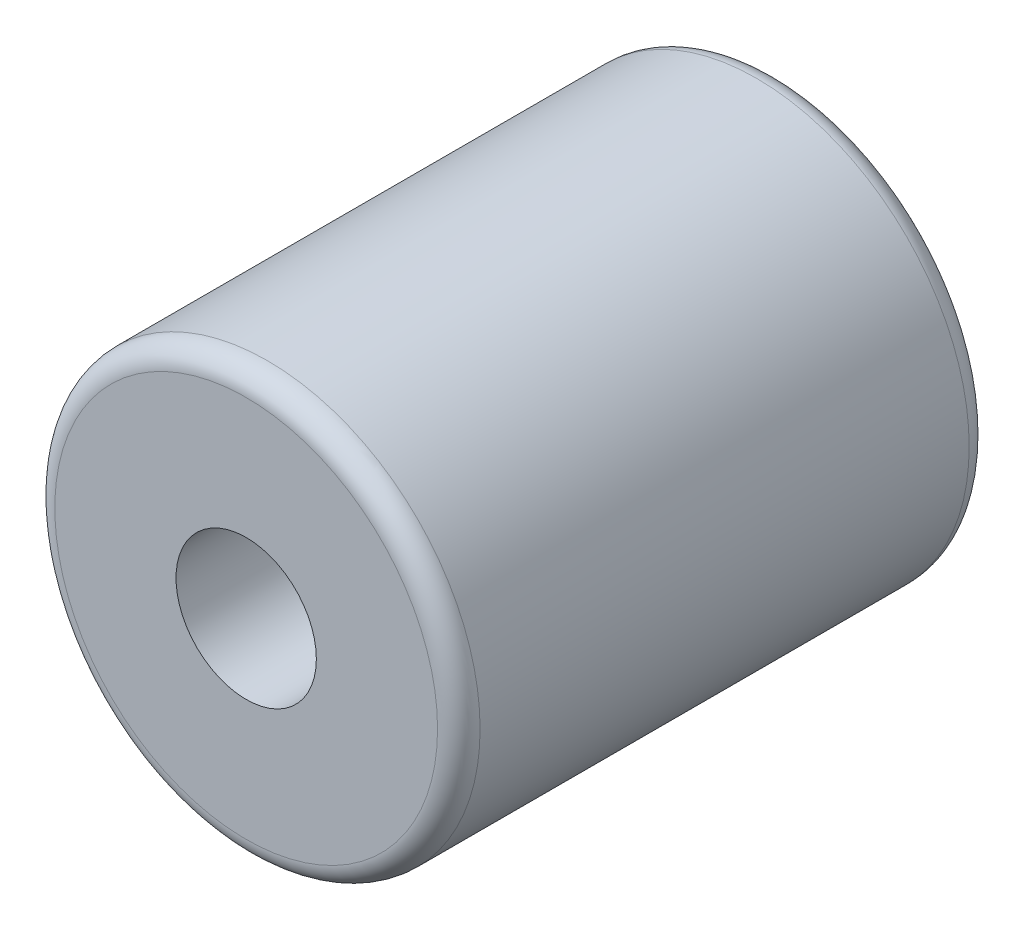
SolidWorks part; units mm, degrees
material "6061 合金"
ref_plane "前视基准面" through (0, 0, 0) normal (0, 0, 1) x (1, 0, 0)
ref_plane "上视基准面" through (0, 0, 0) normal (0, 1, 0) x (1, 0, 0)
ref_plane "右视基准面" through (0, 0, 0) normal (1, 0, 0) x (0, 0, -1)
sketch "草图1" plane through (0, 0, 0) normal (0, 0, 1) x (1, 0, 0)
  circle A0 centre (0, 0) radius 10
  dimension "D1" = 20
extrude "凸台-拉伸1" add sketch "草图1" along normal blind 25
sketch "草图2" plane through (0, 0, 25) normal (0, 0, 1) x (1, 0, 0)
  circle A0 centre (0, 0) radius 3.3
  dimension "D1" = 6.6
extrude "切除-拉伸1" cut sketch "草图2" against normal blind 12
fillet "圆角1" radius 1 2 edges at (10, 0, 25) (10, 0, 0)
sketch "草图3" plane through (0, 0, 0) normal (0, 0, -1) x (-1, 0, 0)
  circle A0 centre (0, 0) radius 2
  dimension "D1" = 4
extrude "切除-拉伸2" cut sketch "草图3" against normal through all
